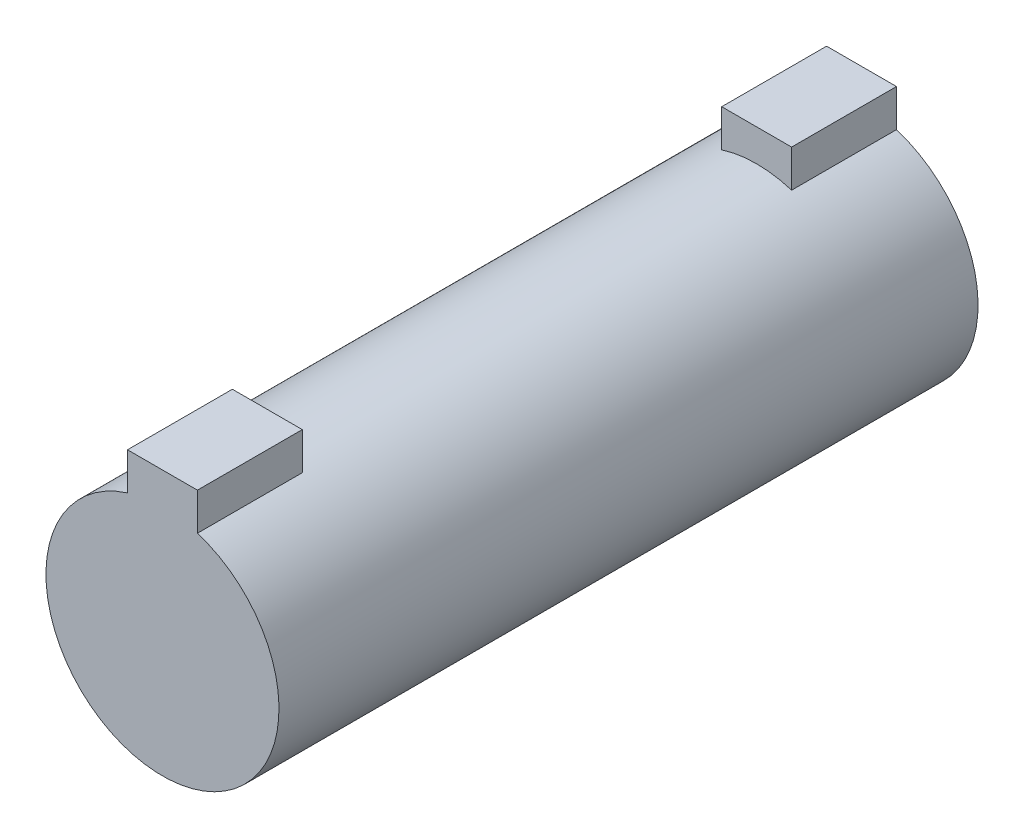
SolidWorks part; units mm, degrees
material "AISI 1010 Steel, hot rolled bar"
ref_plane "Front Plane" through (0, 0, 0) normal (0, 0, 1) x (1, 0, 0)
ref_plane "Top Plane" through (0, 0, 0) normal (0, 1, 0) x (1, 0, 0)
ref_plane "Right Plane" through (0, 0, 0) normal (1, 0, 0) x (0, 0, -1)
sketch "Sketch1" plane through (0, 0, 0) normal (0, 0, 1) x (1, 0, 0)
  circle A0 centre (0, 0) radius 10
  dimension "D1" = 20
extrude "Boss-Extrude1" add sketch "Sketch1" along normal mid plane 60
sketch "Sketch2" plane through (0, 0, 30) normal (0, 0, 1) x (1, 0, 0)
  line L2 (3, 12.745) -> (-3, 12.745)
  line L3 (3, 12.745) -> (3, 9.485)
  line L4 (3, 9.485) -> (-3, 9.485)
  line L5 (-3, 12.745) -> (-3, 9.485)
  line L6 (3, 12.745) -> (-3, 9.485) construction
  line L7 (3, 9.485) -> (-3, 12.745) construction
  point P0 (0, 11.115)
  point P20 (0, 9.485)
  dimension "D1" = 3.26
  dimension "D2" = 6
extrude "Boss-Extrude2" add sketch "Sketch2" against normal blind 9
mirror "Mirror1" about plane through (0, 0, 0) normal (0, 0, 1) of "Boss-Extrude2"
